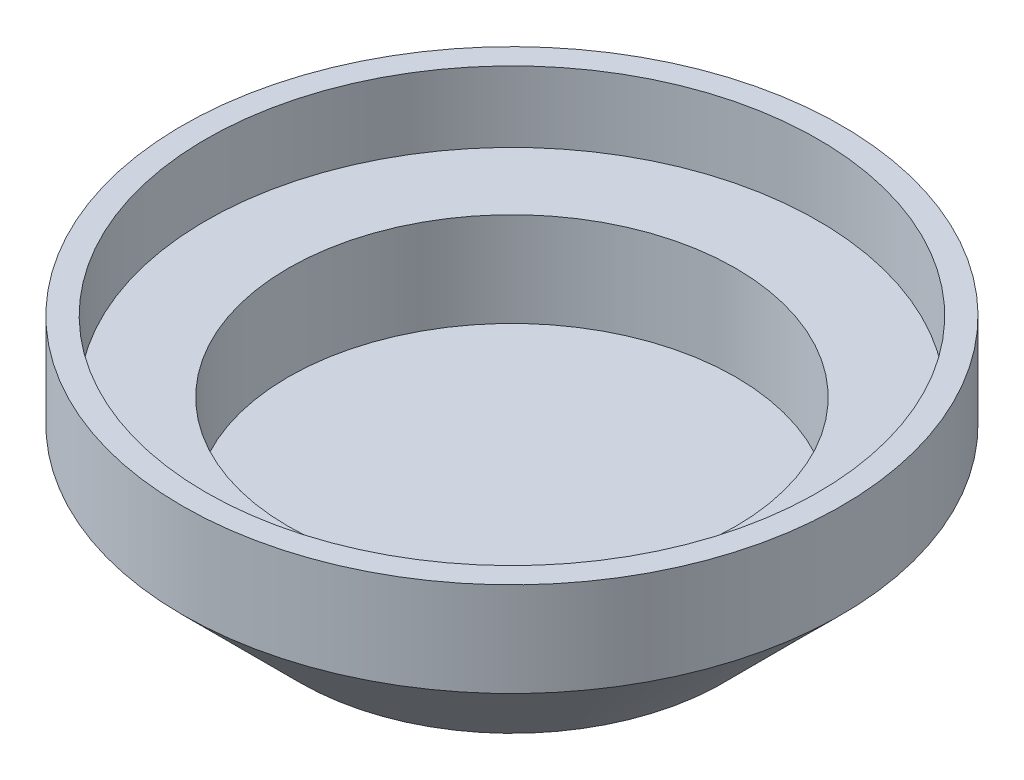
SolidWorks part; units mm, degrees
ref_plane "Front Plane" through (0, 0, 0) normal (0, 0, 1) x (1, 0, 0)
ref_plane "Top Plane" through (0, 0, 0) normal (0, 1, 0) x (1, 0, 0)
ref_plane "Right Plane" through (0, 0, 0) normal (1, 0, 0) x (0, 0, -1)
sketch "Esquisse1" plane through (0, 0, 0) normal (0, 1, 0) x (1, 0, 0)
  circle A0 centre (0, 0) radius 14
extrude "Boss.-Extru.1" add sketch "Esquisse1" along normal blind 9
sketch "Esquisse2" plane through (0, 9, 0) normal (0, 1, 0) x (1, 0, 0)
  circle A0 centre (0, 0) radius 13
extrude "Enlèv. mat.-Extru.1" cut sketch "Esquisse2" against normal blind 3
sketch "Esquisse4" plane through (0, 6, 0) normal (0, 1, 0) x (1, 0, 0)
  circle A0 centre (0, 0) radius 9.5
extrude "Enlèv. mat.-Extru.2" cut sketch "Esquisse4" against normal blind 4
chamfer "Chanfrein1" distance 5 angle 45 1 edges at (0, 0, 14)
